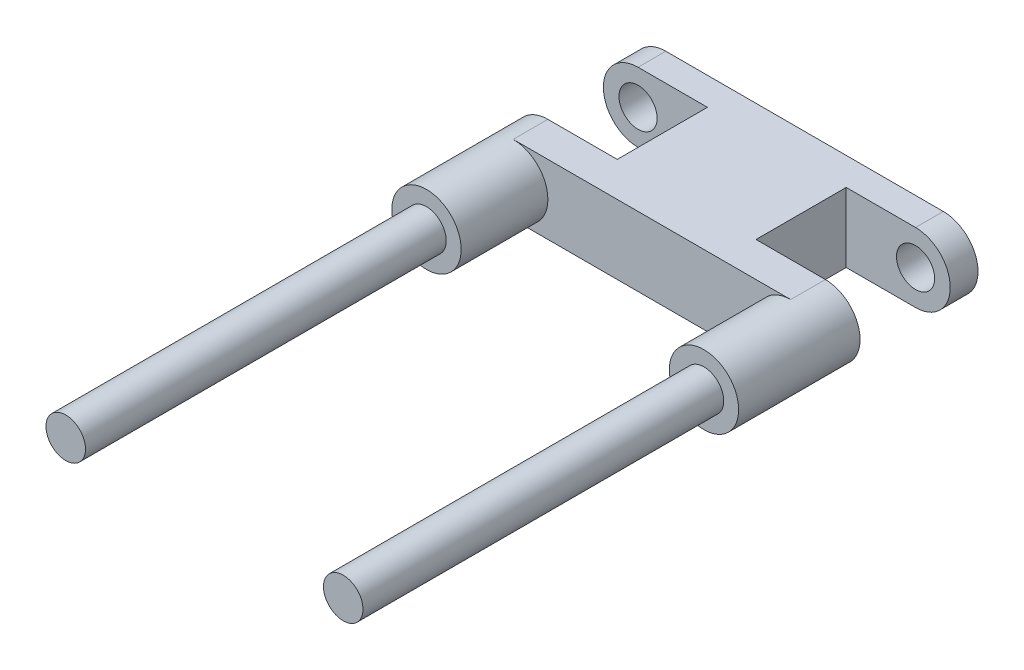
SolidWorks part; units mm, degrees
ref_plane "Front Plane" through (0, 0, 0) normal (0, 0, 1) x (1, 0, 0)
ref_plane "Top Plane" through (0, 0, 0) normal (0, 1, 0) x (1, 0, 0)
ref_plane "Right Plane" through (0, 0, 0) normal (1, 0, 0) x (0, 0, -1)
sketch "Sketch1" plane through (0, 0, 0) normal (0, 0, 1) x (1, 0, 0)
  line L0 (-20, -25) -> (20, -25)
  line L1 (-20, -35) -> (20, -35)
  circle A0 centre (-20, -30) radius 2.75 construction
  circle A1 centre (20, -30) radius 2.75 construction
  circle A2 centre (-20, -30) radius 2.75
  circle A3 centre (20, -30) radius 2.75
  circle A4 centre (20, -30) radius 5
  circle A5 centre (-20, -30) radius 5
  dimension "D1" = 10
  dimension "D2" = 10
extrude "Boss-Extrude1" add sketch "Sketch1" along normal blind 2 contours A5 A2 | A5 L1 A4 L0 | A4 A3
sketch "Sketch2" plane through (0, 0, 2) normal (0, 0, 1) x (1, 0, 0)
  line L0 (0, -25) -> (0, -35)
  line L1 (-20, -25) -> (20, -25) construction
  line L2 (-20, -35) -> (20, -35) construction
  line L3 (-10, -25) -> (-10, -35)
  line L4 (10, -25) -> (10, -35)
  line L5 (-10, -25) -> (10, -25)
  line L6 (10, -35) -> (-10, -35)
  line M4 (-20, -35) -> (20, -35)
  line M6 (20, -25) -> (-20, -25)
  dimension "D1" = 10
  dimension "D2" = 10
extrude "Boss-Extrude2" add sketch "Sketch2" along normal blind 15 contours L3 L0 M6 M4 | L4 L0 M6 M4
sketch "Sketch3" plane through (0, 0, 17) normal (0, 0, 1) x (1, 0, 0)
  line L0 (-10, -35) -> (-10, -25) construction
  line L1 (-10, -25) -> (-20, -25) construction
  line L2 (-20, -35) -> (-10, -35) construction
  line L3 (20, -25) -> (10, -25) construction
  line L4 (10, -25) -> (10, -35) construction
  line L5 (10, -35) -> (20, -35) construction
  line L6 (-10, -35) -> (-10, -25)
  line L7 (-10, -25) -> (-20, -25)
  line L8 (-20, -35) -> (-10, -35)
  line L9 (20, -25) -> (10, -25)
  line L10 (10, -25) -> (10, -35)
  line L11 (10, -35) -> (20, -35)
  line L16 (10, -25) -> (-10, -25)
  line L17 (-10, -25) -> (-10, -35)
  line L18 (-10, -35) -> (10, -35)
  line L19 (10, -35) -> (10, -25)
  line L20 (10, -25) -> (-10, -25)
  line L21 (-10, -25) -> (-10, -35)
  line L22 (-10, -35) -> (10, -35)
  line L23 (10, -35) -> (10, -25)
  arc A0 (-20, -25) -> (-20, -35) centre (-20, -30) ccw construction
  arc A1 (20, -35) -> (20, -25) centre (20, -30) ccw construction
  arc A2 (-20, -25) -> (-20, -35) centre (-20, -30) ccw
  arc A3 (20, -35) -> (20, -25) centre (20, -30) ccw
  circle A4 centre (20, -30) radius 2.75 construction
  circle A5 centre (-20, -30) radius 2.75 construction
  circle A6 centre (20, -30) radius 2.75
  circle A7 centre (-20, -30) radius 2.75
  line M13 (10, -25) -> (-10, -25)
  line M14 (-10, -25) -> (-10, -35)
  line M15 (-10, -35) -> (10, -35)
  line M16 (10, -35) -> (10, -25)
  dimension "D1" = 0
extrude "Boss-Extrude3" add sketch "Sketch3" along normal blind 5 contours L7 A2 L8 A7 M14 | M16 M13 M14 M15 | L11 A3 L9 A6 M16
sketch "Sketch4" plane through (0, 0, 22) normal (0, 0, 1) x (1, 0, 0)
  circle A0 centre (20, -30) radius 5
  circle A1 centre (-20, -30) radius 5
extrude "Boss-Extrude4" add sketch "Sketch4" along normal up to surface (12.5 mm away)
sketch "Sketch5" plane through (0, 0, 34.5) normal (0, 0, 1) x (1, 0, 0)
  circle A0 centre (20, -30) radius 2.85
  circle A1 centre (-20, -30) radius 2.85
  dimension "D1" = 5.7
  dimension "D2" = 5.7
extrude "Boss-Extrude5" add sketch "Sketch5" along normal up to surface (52 mm away)
sketch "Sketch6" plane through (0, 0, 22) normal (0, 0, -1) x (-1, 0, 0)
  circle A1 centre (20, -30) radius 2.75
  circle A2 centre (20, -30) radius 2.75
  circle A3 centre (-20, -30) radius 2.75
  circle A4 centre (-20, -30) radius 2.75
  dimension "D1" = 0
  dimension "D2" = 0
extrude "Boss-Extrude6" add sketch "Sketch6" along normal up to surface (5 mm away) up to face at (16.25, -30, 17)
sketch "Sketch8" plane through (0, 0, 2) normal (0, 0, 1) x (1, 0, 0)
  line L3 (-10, -35) -> (-10, -25)
  line L4 (-10, -25) -> (-20, -25)
  line L5 (-20, -35) -> (-10, -35)
  line L6 (-10, -35) -> (-10, -25)
  line L7 (-10, -25) -> (-20, -25)
  line L8 (-20, -35) -> (-10, -35)
  line L9 (20, -25) -> (10, -25)
  line L10 (10, -25) -> (10, -35)
  line L11 (10, -35) -> (20, -35)
  line L12 (20, -25) -> (10, -25)
  line L13 (10, -25) -> (10, -35)
  line L14 (10, -35) -> (20, -35)
  circle A0 centre (20, -30) radius 2.75 construction
  arc A1 (-20, -25) -> (-20, -35) centre (-20, -30) ccw
  arc A2 (-20, -25) -> (-20, -35) centre (-20, -30) ccw
  arc A3 (20, -35) -> (20, -25) centre (20, -30) ccw
  arc A4 (20, -35) -> (20, -25) centre (20, -30) ccw
  circle A5 centre (20, -30) radius 2.75
  circle A6 centre (-20, -30) radius 2.75 construction
  circle A7 centre (-20, -30) radius 2.75
  dimension "D1" = 0
  dimension "D2" = 0
extrude "Boss-Extrude7" add sketch "Sketch8" along normal blind 2
